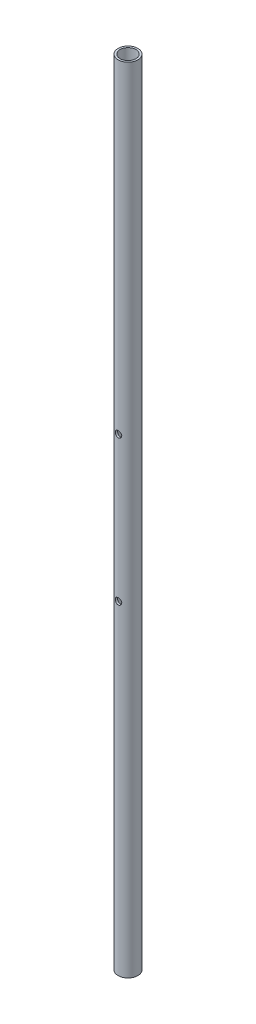
SolidWorks part; units mm, degrees
ref_plane "Plano frontal" through (0, 0, 0) normal (0, 0, 1) x (1, 0, 0)
ref_plane "Plano superior" through (0, 0, 0) normal (0, 1, 0) x (1, 0, 0)
ref_plane "Plano direito" through (0, 0, 0) normal (1, 0, 0) x (0, 0, -1)
sketch "Esboço1" plane through (0, 0, 0) normal (0, 1, 0) x (1, 0, 0)
  circle A0 centre (0, 0) radius 4
  circle A1 centre (0, 0) radius 5
  dimension "D1" = 10
  dimension "D2" = 8
extrude "Ressalto-extrusão1" add sketch "Esboço1" along normal blind 400
sketch "Esboço2" plane through (0, 0, 0) normal (0, 0, 1) x (1, 0, 0)
  line L0 (0, 400) -> (0, 0) construction
  line L1 (5, 400) -> (-5, 400) construction
  line L2 (0, 200) -> (15.5196, 200) construction
  line L3 (15.5196, 200) -> (15.5196, 236.5) construction
  line L4 (15.5196, 236.5) -> (0, 236.5) construction
  circle A0 centre (0, 236.5) radius 1.6
  circle A1 centre (0, 163.5) radius 1.6
  dimension "D2" = 3.2
  dimension "D1" = 36.5
extrude "Corte-extrusão1" cut sketch "Esboço2" against normal through all both and the other way through all
